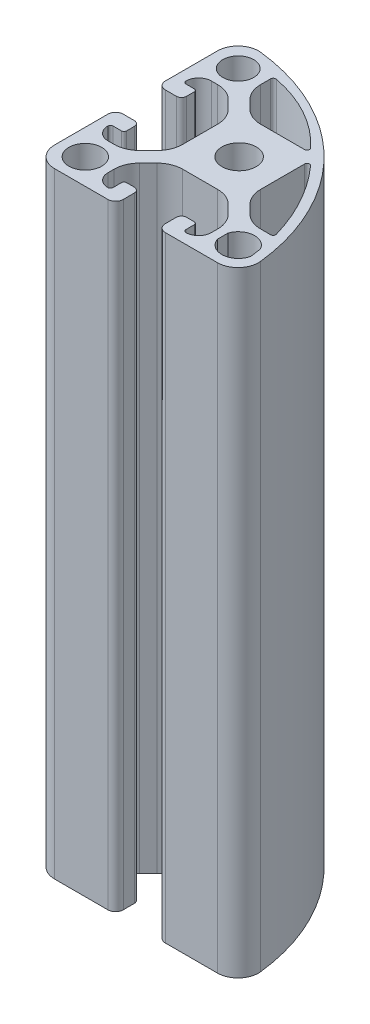
SolidWorks part; units mm, degrees
ref_plane "Alzado" through (0, 0, 0) normal (0, 0, 1) x (1, 0, 0)
ref_plane "Planta" through (0, 0, 0) normal (0, 1, 0) x (1, 0, 0)
ref_plane "Vista lateral" through (0, 0, 0) normal (1, 0, 0) x (0, 0, -1)
sketch "Croquis1" plane through (0, 0, 0) normal (0, 1, 0) x (1, 0, 0)
  line L0 (-18.2, 12.3) -> (-18.2, 15.7771)
  line L1 (-12.3, 11.8) -> (-17.7, 11.8)
  line L2 (-11.8, 16.9053) -> (-11.8, 12.3)
  line L3 (11.8, -17.7) -> (11.8, -12.3)
  line L4 (15.7771, -18.2) -> (12.3, -18.2)
  line L5 (12.3, -11.8) -> (16.9053, -11.8)
  line L6 (-18.2, -16) -> (-18.2, -12.3)
  line L7 (-12.3, -18.2) -> (-16, -18.2)
  line L8 (-11.8, -12.3) -> (-11.8, -17.7)
  line L9 (-17.7, -11.8) -> (-12.3, -11.8)
  line L10 (-10.1, 14.2924) -> (-10.1, 16.2371)
  line L11 (-6.9431, 9.0645) -> (-8.6355, 10.7569)
  line L12 (5.1332, 7.6) -> (-3.4076, 7.6)
  line L13 (4.1, -16.35) -> (4.1, -18.5)
  line L14 (5.6, -20) -> (15.7771, -20)
  line L15 (-20, 15.7771) -> (-20, 5.6)
  line L16 (-18.5, 4.1) -> (-16.35, 4.1)
  line L17 (-15.35, 5.1) -> (-15.35, 6.6)
  line L18 (-15.85, 7.1) -> (-17.5, 7.1)
  line L19 (-15.5, 10.1) -> (-14.2924, 10.1)
  line L20 (-10.7569, 8.6355) -> (-9.0645, 6.9431)
  line L21 (-7.6, 3.4076) -> (-7.6, -3.4076)
  line L22 (-9.0645, -6.9431) -> (-10.7569, -8.6355)
  line L23 (-14.2924, -10.1) -> (-15.5, -10.1)
  line L24 (-17.5, -7.1) -> (-15.85, -7.1)
  line L25 (-15.35, -6.6) -> (-15.35, -5.1)
  line L26 (-16.35, -4.1) -> (-18.5, -4.1)
  line L27 (-20, -5.6) -> (-20, -16)
  line L28 (-16, -20) -> (-5.6, -20)
  line L29 (-4.1, -18.5) -> (-4.1, -16.35)
  line L30 (-5.1, -15.35) -> (-6.6, -15.35)
  line L31 (-7.1, -15.85) -> (-7.1, -17.5)
  line L32 (-10.1, -15.5) -> (-10.1, -14.2924)
  line L33 (-8.6355, -10.7569) -> (-6.9431, -9.0645)
  line L34 (-3.4076, -7.6) -> (3.4076, -7.6)
  line L35 (6.9431, -9.0645) -> (8.6355, -10.7569)
  line L36 (10.1, -14.2924) -> (10.1, -15.5)
  line L37 (7.1, -17.5) -> (7.1, -15.85)
  line L38 (6.6, -15.35) -> (5.1, -15.35)
  line L39 (16.2371, -10.1) -> (14.2924, -10.1)
  line L40 (10.7569, -8.6355) -> (9.0645, -6.9431)
  line L41 (7.6, -3.4076) -> (7.6, 5.1332)
  circle A0 centre (0, 0) radius 3.35
  arc A1 (-15.7556, 17.9635) -> (-18.2, 15.7771) centre (-16, 15.7771) ccw
  arc A2 (-18.2, 12.3) -> (-17.7, 11.8) centre (-17.7, 12.3) ccw
  arc A3 (-12.3, 11.8) -> (-11.8, 12.3) centre (-12.3, 12.3) ccw
  arc A4 (-11.8, 16.9053) -> (-12.1979, 17.3947) centre (-12.3, 16.9053) ccw
  arc A5 (-12.1979, 17.3947) -> (-15.7556, 17.9635) centre (-20, -20) ccw
  arc A6 (12.3, -11.8) -> (11.8, -12.3) centre (12.3, -12.3) ccw
  arc A7 (11.8, -17.7) -> (12.3, -18.2) centre (12.3, -17.7) ccw
  arc A8 (15.7771, -18.2) -> (17.9635, -15.7556) centre (15.7771, -16) ccw
  arc A9 (17.9635, -15.7556) -> (17.3947, -12.1979) centre (-20, -20) ccw
  arc A10 (17.3947, -12.1979) -> (16.9053, -11.8) centre (16.9053, -12.3) ccw
  arc A11 (-17.7, -11.8) -> (-18.2, -12.3) centre (-17.7, -12.3) ccw
  arc A12 (-18.2, -16) -> (-16, -18.2) centre (-16, -16) ccw
  arc A13 (-12.3, -18.2) -> (-11.8, -17.7) centre (-12.3, -17.7) ccw
  arc A14 (-11.8, -12.3) -> (-12.3, -11.8) centre (-12.3, -12.3) ccw
  arc A15 (4.1, -18.5) -> (5.6, -20) centre (5.6, -18.5) ccw
  arc A16 (15.7771, -20) -> (19.7523, -15.5556) centre (15.7771, -16) ccw
  arc A17 (19.7523, -15.5556) -> (-15.5556, 19.7523) centre (-20, -20) ccw
  arc A18 (-15.5556, 19.7523) -> (-20, 15.7771) centre (-16, 15.7771) ccw
  arc A19 (-20, 5.6) -> (-18.5, 4.1) centre (-18.5, 5.6) ccw
  arc A20 (-16.35, 4.1) -> (-15.35, 5.1) centre (-16.35, 5.1) ccw
  arc A21 (-15.35, 6.6) -> (-15.85, 7.1) centre (-15.85, 6.6) ccw
  arc A22 (-18, 7.6) -> (-17.5, 7.1) centre (-17.5, 7.6) ccw
  arc A23 (-15.5, 10.1) -> (-18, 7.6) centre (-15.5, 7.6) ccw
  arc A24 (-10.7569, 8.6355) -> (-14.2924, 10.1) centre (-14.2924, 5.1) ccw
  arc A25 (-7.6, 3.4076) -> (-9.0645, 6.9431) centre (-12.6, 3.4076) ccw
  arc A26 (-9.0645, -6.9431) -> (-7.6, -3.4076) centre (-12.6, -3.4076) ccw
  arc A27 (-14.2924, -10.1) -> (-10.7569, -8.6355) centre (-14.2924, -5.1) ccw
  arc A28 (-18, -7.6) -> (-15.5, -10.1) centre (-15.5, -7.6) ccw
  arc A29 (-17.5, -7.1) -> (-18, -7.6) centre (-17.5, -7.6) ccw
  arc A30 (-15.85, -7.1) -> (-15.35, -6.6) centre (-15.85, -6.6) ccw
  arc A31 (-15.35, -5.1) -> (-16.35, -4.1) centre (-16.35, -5.1) ccw
  arc A32 (-18.5, -4.1) -> (-20, -5.6) centre (-18.5, -5.6) ccw
  arc A33 (-20, -16) -> (-16, -20) centre (-16, -16) ccw
  arc A34 (-5.6, -20) -> (-4.1, -18.5) centre (-5.6, -18.5) ccw
  arc A35 (-4.1, -16.35) -> (-5.1, -15.35) centre (-5.1, -16.35) ccw
  arc A36 (-6.6, -15.35) -> (-7.1, -15.85) centre (-6.6, -15.85) ccw
  arc A37 (-7.6, -18) -> (-7.1, -17.5) centre (-7.6, -17.5) ccw
  arc A38 (-10.1, -15.5) -> (-7.6, -18) centre (-7.6, -15.5) ccw
  arc A39 (-8.6355, -10.7569) -> (-10.1, -14.2924) centre (-5.1, -14.2924) ccw
  arc A40 (-3.4076, -7.6) -> (-6.9431, -9.0645) centre (-3.4076, -12.6) ccw
  arc A41 (6.9431, -9.0645) -> (3.4076, -7.6) centre (3.4076, -12.6) ccw
  arc A42 (10.1, -14.2924) -> (8.6355, -10.7569) centre (5.1, -14.2924) ccw
  arc A43 (7.6, -18) -> (10.1, -15.5) centre (7.6, -15.5) ccw
  arc A44 (7.1, -17.5) -> (7.6, -18) centre (7.6, -17.5) ccw
  arc A45 (7.1, -15.85) -> (6.6, -15.35) centre (6.6, -15.85) ccw
  arc A46 (5.1, -15.35) -> (4.1, -16.35) centre (5.1, -16.35) ccw
  arc A47 (-9.4621, 16.7177) -> (-10.1, 16.2371) centre (-9.6, 16.2371) ccw
  arc A48 (-10.1, 14.2924) -> (-8.6355, 10.7569) centre (-5.1, 14.2924) ccw
  arc A49 (-6.9431, 9.0645) -> (-3.4076, 7.6) centre (-3.4076, 12.6) ccw
  arc A50 (5.1332, 7.6) -> (5.4666, 8.4727) centre (5.1332, 8.1) ccw
  arc A51 (16.7177, -9.4621) -> (8.4727, 5.4666) centre (-20, -20) ccw
  arc A52 (16.2371, -10.1) -> (16.7177, -9.4621) centre (16.2371, -9.6) ccw
  arc A53 (10.7569, -8.6355) -> (14.2924, -10.1) centre (14.2924, -5.1) ccw
  arc A54 (7.6, -3.4076) -> (9.0645, -6.9431) centre (12.6, -3.4076) ccw
  arc A55 (8.4727, 5.4666) -> (7.6, 5.1332) centre (8.1, 5.1332) ccw
  arc A56 (-9.4621, 16.7177) -> (5.4666, 8.4727) centre (-14.5044, -10.0495) cw
extrude "Saliente-Extruir1" add sketch "Croquis1" along normal blind 120
sketch "Croquis2" plane through (0, 120, 0) normal (0, 1, 0) x (1, 0, 0)
  line L0 (-18.2, 15.7771) -> (-18.2, 12.3) construction
  line L1 (-17.7, 11.8) -> (-12.3, 11.8) construction
  line L2 (-11.8, 12.3) -> (-11.8, 16.9053) construction
  line L3 (-18.2, 15.7771) -> (-18.2, 12.3)
  line L4 (-17.7, 11.8) -> (-12.3, 11.8)
  line L5 (-11.8, 12.3) -> (-11.8, 16.9053)
  line L6 (-16, -18.2) -> (-12.3, -18.2) construction
  line L7 (-18.2, -12.3) -> (-18.2, -16) construction
  line L8 (-12.3, -11.8) -> (-17.7, -11.8) construction
  line L9 (-11.8, -17.7) -> (-11.8, -12.3) construction
  line L10 (-16, -18.2) -> (-12.3, -18.2)
  line L11 (-18.2, -12.3) -> (-18.2, -16)
  line L12 (-12.3, -11.8) -> (-17.7, -11.8)
  line L13 (-11.8, -17.7) -> (-11.8, -12.3)
  line L14 (12.3, -18.2) -> (15.7771, -18.2) construction
  line L15 (11.8, -12.3) -> (11.8, -17.7) construction
  line L16 (16.9053, -11.8) -> (12.3, -11.8) construction
  line L17 (12.3, -18.2) -> (15.7771, -18.2)
  line L18 (11.8, -12.3) -> (11.8, -13.9666)
  line L19 (16.9053, -11.8) -> (12.3, -11.8)
  line L20 (11.8, -16.0334) -> (11.8, -17.7)
  arc A0 (-11.8, 16.9053) -> (-12.1979, 17.3947) centre (-12.3, 16.9053) ccw construction
  arc A1 (-12.1979, 17.3947) -> (-15.7556, 17.9635) centre (-20, -20) ccw construction
  arc A2 (-15.7556, 17.9635) -> (-18.2, 15.7771) centre (-16, 15.7771) ccw construction
  arc A3 (-18.2, 12.3) -> (-17.7, 11.8) centre (-17.7, 12.3) ccw construction
  arc A4 (-12.3, 11.8) -> (-11.8, 12.3) centre (-12.3, 12.3) ccw construction
  arc A5 (-11.8, 16.9053) -> (-12.1979, 17.3947) centre (-12.3, 16.9053) ccw
  arc A6 (-12.1979, 17.3947) -> (-15.7556, 17.9635) centre (-20, -20) ccw
  arc A7 (-15.7556, 17.9635) -> (-18.2, 15.7771) centre (-16, 15.7771) ccw
  arc A8 (-18.2, 12.3) -> (-17.7, 11.8) centre (-17.7, 12.3) ccw
  arc A9 (-12.3, 11.8) -> (-11.8, 12.3) centre (-12.3, 12.3) ccw
  arc A10 (-12.3, -18.2) -> (-11.8, -17.7) centre (-12.3, -17.7) ccw construction
  arc A11 (-18.2, -16) -> (-16, -18.2) centre (-16, -16) ccw construction
  arc A12 (-17.7, -11.8) -> (-18.2, -12.3) centre (-17.7, -12.3) ccw construction
  arc A13 (-11.8, -12.3) -> (-12.3, -11.8) centre (-12.3, -12.3) ccw construction
  arc A14 (-12.3, -18.2) -> (-11.8, -17.7) centre (-12.3, -17.7) ccw
  arc A15 (-18.2, -16) -> (-16, -18.2) centre (-16, -16) ccw
  arc A16 (-17.7, -11.8) -> (-18.2, -12.3) centre (-17.7, -12.3) ccw
  arc A17 (-11.8, -12.3) -> (-12.3, -11.8) centre (-12.3, -12.3) ccw
  arc A18 (17.3947, -12.1979) -> (16.9053, -11.8) centre (16.9053, -12.3) ccw construction
  arc A19 (17.9635, -15.7556) -> (17.3947, -12.1979) centre (-20, -20) ccw construction
  arc A20 (15.7771, -18.2) -> (17.9635, -15.7556) centre (15.7771, -16) ccw construction
  arc A21 (11.8, -17.7) -> (12.3, -18.2) centre (12.3, -17.7) ccw construction
  arc A22 (12.3, -11.8) -> (11.8, -12.3) centre (12.3, -12.3) ccw construction
  arc A23 (17.3947, -12.1979) -> (16.9053, -11.8) centre (16.9053, -12.3) ccw
  arc A24 (17.9635, -15.7556) -> (17.9551, -15.6816) centre (-20, -20) ccw
  arc A25 (15.7771, -18.2) -> (17.9635, -15.7556) centre (15.7771, -16) ccw
  arc A26 (11.8, -17.7) -> (12.3, -18.2) centre (12.3, -17.7) ccw
  arc A27 (12.3, -11.8) -> (11.8, -12.3) centre (12.3, -12.3) ccw
  circle A28 centre (-14.9928, 14.8209) radius 3.0209
  circle A29 centre (-15, -15) radius 3.2
  circle A30 centre (14.8285, -15) radius 3.2
  arc A31 (17.6371, -13.4664) -> (17.3947, -12.1979) centre (-20, -20) ccw
extrude "Saliente-Extruir2" add sketch "Croquis2" against normal up to surface (120 mm away) contours A29 L13 A17 L12 | A29 L10 A14 L13 | A29 L11 A15 L10 | A29 L12 A16 L11 | A28 A6 A7 L3 A8 L4 | A28 L4 A9 L5 A5 A6 | A30 A31 A23 L19 | A30 L19 A27 L18 | A30 L20 A26 L17 | A30 L17 A25 A24 up to face at (-4.7129, 0, -11.4358)
